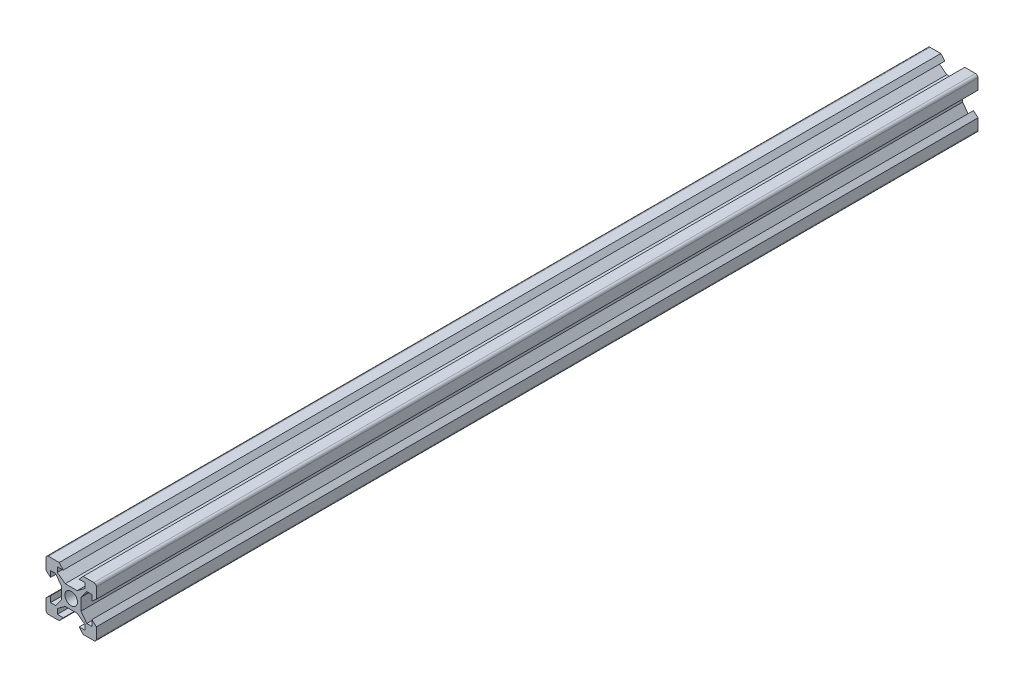
SolidWorks part; units mm, degrees
ref_plane "Front Plane" through (0, 0, 0) normal (0, 0, 1) x (1, 0, 0)
ref_plane "Top Plane" through (0, 0, 0) normal (0, 1, 0) x (1, 0, 0)
ref_plane "Right Plane" through (0, 0, 0) normal (1, 0, 0) x (0, 0, -1)
sketch "Sketch1" plane through (0, 0, 0) normal (0, 0, 1) x (1, 0, 0)
  line L0 (-5.5, 8.2) -> (-3.15, 8.2)
  line L5 (-10, -10) -> (10, 10) construction
  line L6 (-10, 10) -> (10, -10) construction
  line L7 (-9, 10) -> (-4.75, 10)
  line L8 (4.75, 10) -> (9, 10)
  line L9 (-4.75, 10) -> (-3.15, 8.2)
  line L10 (4.75, 10) -> (3.15, 8.2)
  line L11 (3.15, 8.2) -> (5.5, 8.2)
  line L12 (-5.5, 8.2) -> (-5.5, 6.2)
  line L13 (5.5, 8.2) -> (5.5, 6.2)
  line L14 (2.3879, 3.9) -> (-2.3879, 3.9)
  line L15 (-5.5, 6.2) -> (-2.3879, 3.9)
  line L16 (2.3879, 3.9) -> (5.5, 6.2)
  line L17 (10, 9) -> (10, 4.75)
  line L18 (10, 4.75) -> (8.2, 3.15)
  line L19 (10, -4.75) -> (8.2, -3.15)
  line L20 (8.2, -3.15) -> (8.2, -5.5)
  line L21 (8.2, 5.5) -> (8.2, 3.15)
  line L22 (8.2, 5.5) -> (6.2, 5.5)
  line L23 (6.2, 5.5) -> (3.9, 2.3879)
  line L24 (3.9, -2.3879) -> (3.9, 2.3879)
  line L25 (3.9, -2.3879) -> (6.2, -5.5)
  line L26 (8.2, -5.5) -> (6.2, -5.5)
  line L27 (10, -4.75) -> (10, -9)
  line L28 (9, -10) -> (4.75, -10)
  line L29 (4.75, -10) -> (3.15, -8.2)
  line L30 (-4.75, -10) -> (-3.15, -8.2)
  line L31 (-3.15, -8.2) -> (-5.5, -8.2)
  line L32 (5.5, -8.2) -> (3.15, -8.2)
  line L33 (5.5, -8.2) -> (5.5, -6.2)
  line L34 (5.5, -6.2) -> (2.3879, -3.9)
  line L35 (-2.3879, -3.9) -> (2.3879, -3.9)
  line L36 (-2.3879, -3.9) -> (-5.5, -6.2)
  line L37 (-5.5, -8.2) -> (-5.5, -6.2)
  line L38 (-4.75, -10) -> (-9, -10)
  line L39 (-10, -9) -> (-10, -4.75)
  line L40 (-10, -4.75) -> (-8.2, -3.15)
  line L41 (-10, 4.75) -> (-8.2, 3.15)
  line L42 (-8.2, 3.15) -> (-8.2, 5.5)
  line L43 (-8.2, -5.5) -> (-8.2, -3.15)
  line L44 (-8.2, -5.5) -> (-6.2, -5.5)
  line L45 (-6.2, -5.5) -> (-3.9, -2.3879)
  line L46 (-3.9, 2.3879) -> (-3.9, -2.3879)
  line L47 (-3.9, 2.3879) -> (-6.2, 5.5)
  line L48 (-8.2, 5.5) -> (-6.2, 5.5)
  line L49 (-10, 4.75) -> (-10, 9)
  arc A0 (9, 10) -> (10, 9) centre (9, 9) cw
  arc A1 (9, -10) -> (10, -9) centre (9, -9) ccw
  arc A2 (-9, -10) -> (-10, -9) centre (-9, -9) cw
  arc A3 (-10, 9) -> (-9, 10) centre (-9, 9) cw
  circle A4 centre (0, 0) radius 2.5
  point P0 (0, 0)
  point P21 (0, 10)
  point P24 (0, 8.2)
  point P27 (0, 8.2)
  point P32 (0, 3.9)
  point P71 (0, 0)
  dimension "D3" = 1
  dimension "D12" = 5
  dimension "D1" = 20
  dimension "D2" = 20
  dimension "D4" = 9.5
  dimension "D5" = 6.3
  dimension "D6" = 0
  dimension "D7" = 10
  dimension "D8" = 6.1
  dimension "D9" = 11
  dimension "D10" = 2
  dimension "D11" = 4
extrude "Boss-Extrude1" add sketch "Sketch1" along normal blind 350
